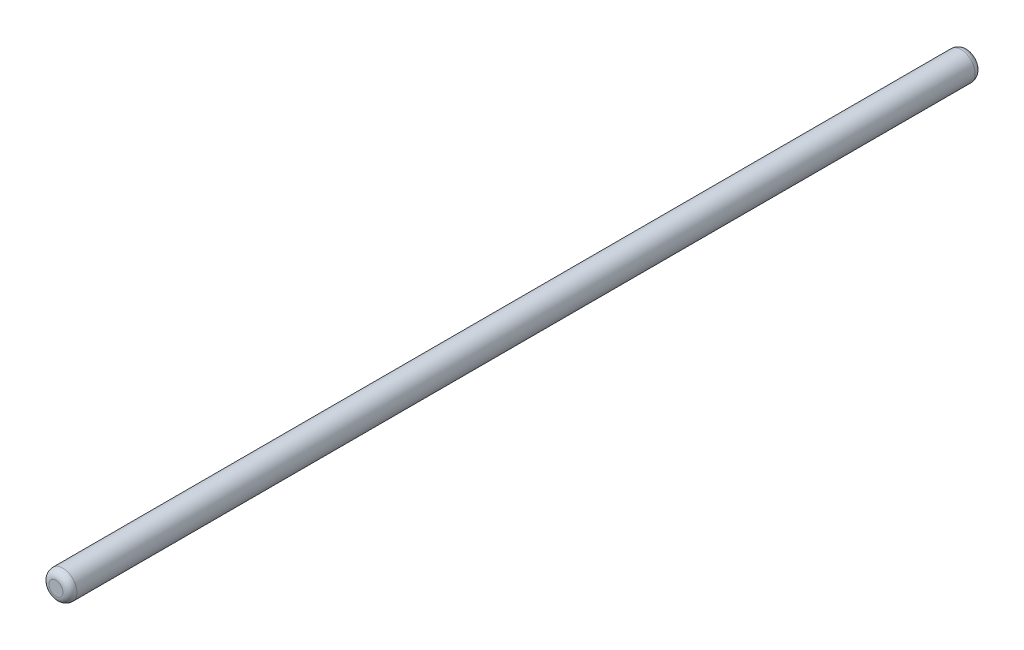
SolidWorks part; units mm, degrees
ref_plane "Front Plane" through (0, 0, 0) normal (0, 0, 1) x (1, 0, 0)
ref_plane "Top Plane" through (0, 0, 0) normal (0, 1, 0) x (1, 0, 0)
ref_plane "Right Plane" through (0, 0, 0) normal (1, 0, 0) x (0, 0, -1)
sketch "Sketch1" plane through (0, 0, 0) normal (0, 0, 1) x (1, 0, 0)
  circle A0 centre (0, 0) radius 4
  dimension "D1" = 8
extrude "Boss-Extrude1" add sketch "Sketch1" along normal blind 260.525
fillet "Fillet1" radius 2 2 edges at (4, 0, 260.525) (4, 0, 0)
